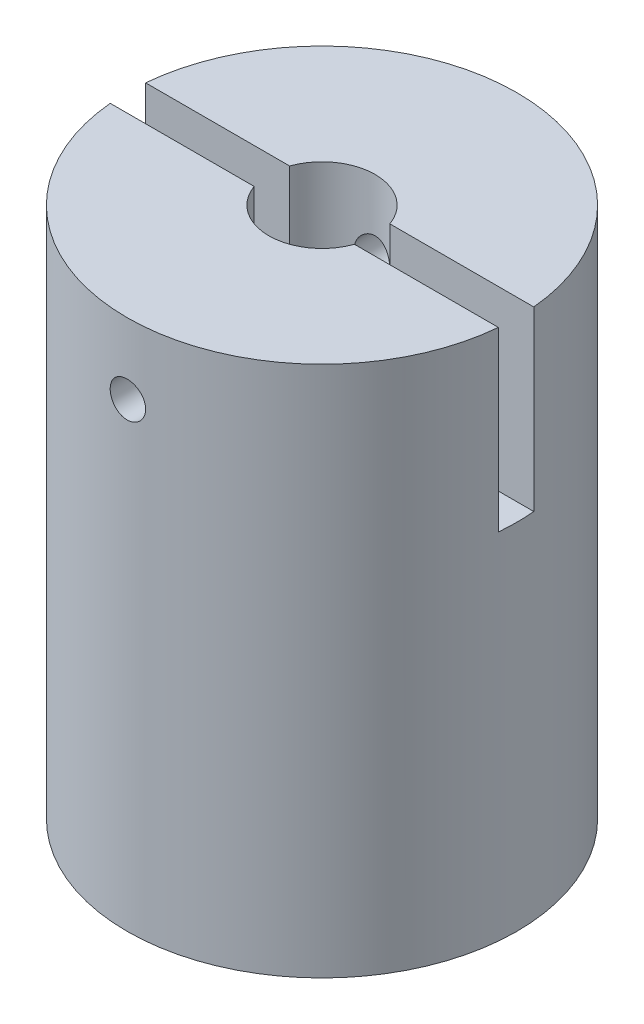
SolidWorks part; units mm, degrees
material "Kiefer"
ref_plane "Ebene vorne" through (0, 0, 0) normal (0, 0, 1) x (1, 0, 0)
ref_plane "Ebene oben" through (0, 0, 0) normal (0, 1, 0) x (1, 0, 0)
ref_plane "Ebene rechts" through (0, 0, 0) normal (1, 0, 0) x (0, 0, -1)
sketch "Skizze1" plane through (0, 0, 0) normal (0, 1, 0) x (1, 0, 0)
  circle A0 centre (0, 0) radius 11
  dimension "D1" = 22
extrude "Aufsatz-Linear austragen1" add sketch "Skizze1" along normal blind 30
sketch "Skizze2" plane through (0, 30, 0) normal (0, 1, 0) x (1, 0, 0)
  circle A0 centre (0, 0) radius 3
  dimension "D1" = 6
extrude "Schnitt-Linear austragen1" cut sketch "Skizze2" against normal through all
sketch "Skizze3" plane through (0, 30, 0) normal (0, 1, 0) x (1, 0, 0)
  line L1 (-15, 1) -> (15, 1)
  line L2 (-15, 1) -> (-15, -1)
  line L3 (-15, -1) -> (15, -1)
  line L4 (15, 1) -> (15, -1)
  line L5 (-15, 1) -> (15, -1) construction
  line L6 (-15, -1) -> (15, 1) construction
  point P0 (0, 0)
  dimension "D1" = 30
  dimension "D2" = 2
extrude "Schnitt-Linear austragen2" cut sketch "Skizze3" against normal blind 10
sketch "Skizze4" plane through (0, 0, -1) normal (0, 0, 1) x (1, 0, 0)
  line L0 (0, 0) -> (0, 30) construction
  line L1 (10.9545, 30) -> (-10.9545, 30) construction
  circle A0 centre (0, 26) radius 1
  dimension "D1" = 2
  dimension "D2" = 4
extrude "Schnitt-Linear austragen3" cut sketch "Skizze4" against normal through all both and the other way through all
sketch "Skizze5" plane through (0, 0, 0) normal (0, -1, 0) x (1, 0, 0)
  line L0 (0, -7.5) -> (0, 7.5) construction
  circle A0 centre (0, 7.5) radius 1
  circle A1 centre (0, -7.5) radius 1
  point P4 (0, 0)
  dimension "D1" = 2
  dimension "D2" = 15
extrude "Schnitt-Linear austragen4" cut sketch "Skizze5" against normal blind 10
